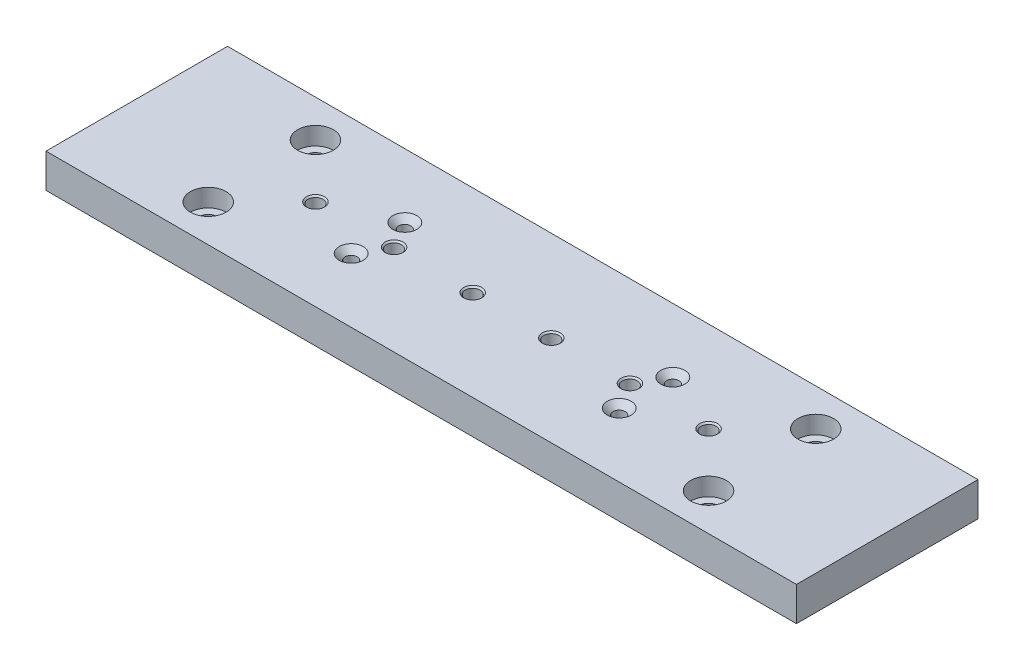
SolidWorks part; units mm, degrees
material "6061-T6 (SS)"
ref_plane "Front" through (0, 0, 0) normal (0, 0, 1) x (1, 0, 0)
ref_plane "Top" through (0, 0, 0) normal (0, 1, 0) x (1, 0, 0)
ref_plane "Right" through (0, 0, 0) normal (1, 0, 0) x (0, 0, -1)
sketch "Sketch1" plane through (0, 0, 0) normal (0, 1, 0) x (1, 0, 0)
  line L0 (0, 12.5629) -> (0, -12.5629) construction
  line L1 (-105, -25.4) -> (105, -25.4)
  line L2 (-105, -25.4) -> (-105, 25.4)
  line L3 (-105, 25.4) -> (105, 25.4)
  line L4 (105, -25.4) -> (105, 25.4)
  line L5 (-105, -25.4) -> (105, 25.4) construction
  line L6 (-105, 25.4) -> (105, -25.4) construction
  line L7 (-55, -20) -> (55, -20) construction
  line L8 (-55, -20) -> (-55, 20) construction
  line L9 (-55, 20) -> (55, 20) construction
  line L10 (55, -20) -> (55, 20) construction
  line L11 (-55, -20) -> (55, 20) construction
  line L12 (-55, 20) -> (55, -20) construction
  line L13 (-80, 25.4) -> (-60, 25.4) construction
  line L14 (-80, 25.4) -> (-80, -25.4) construction
  line L15 (-80, -25.4) -> (-60, -25.4) construction
  line L16 (-60, 25.4) -> (-60, -25.4) construction
  line L17 (60, 25.4) -> (60, -25.4) construction
  line L18 (80, -25.4) -> (60, -25.4) construction
  line L19 (80, 25.4) -> (80, -25.4) construction
  line L20 (80, 25.4) -> (60, 25.4) construction
  point P0 (0, 0)
  point P6 (0, 0)
  dimension "D1" = 40
  dimension "D2" = 110
  dimension "D3" = 50.8
  dimension "D4" = 20
  dimension "D5" = 5
  dimension "D6" = 25
extrude "Boss-Extrude1" add sketch "Sketch1" along normal blind 9.525
hole_wizard "CSK for M3 SFHCS1" positions "Sketch2" profile "Sketch3" countersink size "M3" standard "ANSI Metric" end condition through all
sketch "Sketch2" plane through (0, 9.525, 0) normal (0, 1, 0) x (1, 0, 0)
  line L0 (-37.5, 7.5) -> (37.5, -7.5) construction
  line L2 (-55, -20) -> (-55, 20) construction
  point P1 (-37.5, 7.5)
  point P3 (-37.5, -7.5)
  point P5 (37.5, -7.5)
  point P7 (37.5, 7.5)
  dimension "D1" = 15
  dimension "D2" = 17.5
sketch "Sketch3" plane through (-37.5, 9.525, -7.5) normal (1, 0, 0) x (0, 0, 1)
  line L0 (0, 0) -> (0, 9.525)
  line L1 (0, 9.525) -> (1.7, 9.525)
  line L2 (1.7, 9.525) -> (1.7, 1.66)
  line L3 (1.7, 1.66) -> (3.36, 0)
  line L5 (3.36, 0) -> (0, 0)
  line L6 (-1.7, 1.66) -> (-3.36, 0) construction
  line L11 (0, -6.35) -> (0, 107.95) construction
  dimension "Thru Hole Dia." = 3.4
  dimension "Thru Hole Depth" = 9.525
  dimension "Near C'Sink Dia." = 6.72
  dimension "Near C'Sink Angle" = 90
hole_wizard "CBORE for M5 SHCS1" positions "Sketch4" profile "Sketch5" counterbore size "M5" standard "ANSI Metric" end condition through all
sketch "Sketch4" plane through (0, 9.525, 0) normal (0, 1, 0) x (1, 0, 0)
  line L0 (-80, 0) -> (-60, 0)
  line L1 (-80, 25.4) -> (-80, -25.4) construction
  line L2 (-60, 25.4) -> (-60, -25.4) construction
  line L4 (-70, 15) -> (-70, -15)
  point P9 (-70, 15)
  point P10 (-70, -15)
  point P13 (-70, 0)
  dimension "D1" = 30
sketch "Sketch5" plane through (-70, 9.525, 15) normal (1, 0, 0) x (0, 0, 1)
  line L0 (0, 0) -> (0, 9.525)
  line L1 (0, 9.525) -> (2.75, 9.525)
  line L3 (2.75, 9.525) -> (2.75, 5)
  line L4 (2.75, 5) -> (5, 5)
  line L5 (5, 5) -> (5, 0)
  line L7 (5, 0) -> (0, 0)
  line L11 (0, -6.35) -> (0, 107.95) construction
  dimension "Thru Hole Dia." = 5.5
  dimension "Thru Hole Depth" = 9.525
  dimension "C'Bore Dia." = 10
  dimension "C'Bore Depth" = 5
mirror "Mirror1" about plane through (0, 0, 0) normal (1, 0, 0) of "CBORE for M5 SHCS1"
hole_wizard "M5x0.8 Tapped Hole1" positions "Sketch6" profile "Sketch8" tap size "M5x0.8" standard "ANSI Metric" end condition through all
sketch "Sketch6" plane through (0, 9.525, 0) normal (0, 1, 0) x (1, 0, 0)
  point P0 (-55, 0)
  point P7 (-33, 0)
  point P8 (-11, 0)
  point P9 (11, 0)
  point P10 (33, 0)
  point P11 (55, 0)
  dimension "D2" = 55
  dimension "D3" = 55
  dimension "D1" = 6
sketch "Sketch8" plane through (-55, 9.525, 0) normal (1, 0, 0) x (0, 0, 1)
  line L0 (0, 0) -> (0, 9.525)
  line L1 (0, 9.525) -> (2.1, 9.525)
  line L2 (2.1, 9.525) -> (2.1, 0.425)
  line L3 (2.1, 0.425) -> (2.525, 0)
  line L5 (2.525, 0) -> (0, 0)
  line L6 (-2.1, 0.425) -> (-2.525, 0) construction
  line L11 (0, -6.35) -> (0, 107.95) construction
  dimension "Thru Tap Drill Dia." = 4.2
  dimension "Thru Tap Drill Depth" = 9.525
  dimension "Near C'Sink Dia." = 5.05
  dimension "Near C'Sink Angle" = 90
cosmetic thread "Hole Thread1" parameters "D2"=5
cosmetic thread "Hole Thread2" parameters "D2"=5
cosmetic thread "Hole Thread3" parameters "D2"=5
cosmetic thread "Hole Thread4" parameters "D2"=5
cosmetic thread "Hole Thread5" parameters "D2"=5
cosmetic thread "Hole Thread6" parameters "D2"=5
